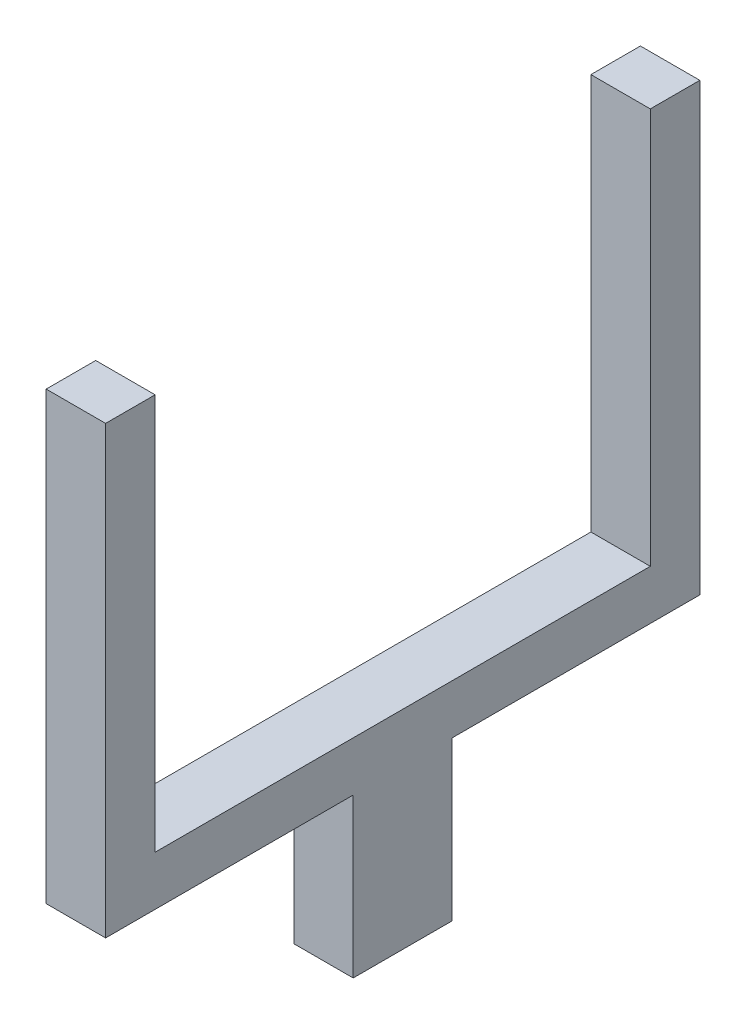
SolidWorks part; units mm, degrees
ref_plane "Front Plane" through (0, 0, 0) normal (0, 0, 1) x (1, 0, 0)
ref_plane "Top Plane" through (0, 0, 0) normal (0, 1, 0) x (1, 0, 0)
ref_plane "Right Plane" through (0, 0, 0) normal (1, 0, 0) x (0, 0, -1)
sketch "Sketch1" plane through (0, 0, 0) normal (1, 0, 0) x (0, 0, -1)
  line L12 (0, 0) -> (0, 22.092) construction
  line L13 (2.5, 0) -> (-2.5, 0)
  line L14 (-2.5, 0) -> (-2.5, 8)
  line L15 (-2.5, 8) -> (-15, 8)
  line L16 (-15, 8) -> (-15, 30.5)
  line L17 (-15, 30.5) -> (-12.5, 30.5)
  line L18 (-12.5, 30.5) -> (-12.5, 10.5)
  line L19 (-12.5, 10.5) -> (12.5, 10.5)
  line L20 (12.5, 30.5) -> (12.5, 10.5)
  line L21 (15, 30.5) -> (12.5, 30.5)
  line L22 (15, 8) -> (15, 30.5)
  line L23 (2.5, 8) -> (15, 8)
  line L24 (2.5, 0) -> (2.5, 8)
  point P11 (0, 10.5)
  dimension "D1" = 2.5
  dimension "D2" = 8
  dimension "D3" = 12.5
  dimension "D4" = 2.5
  dimension "D5" = 20
  dimension "D6" = 22.5
extrude "Boss-Extrude1" add sketch "Sketch1" along normal blind 3
